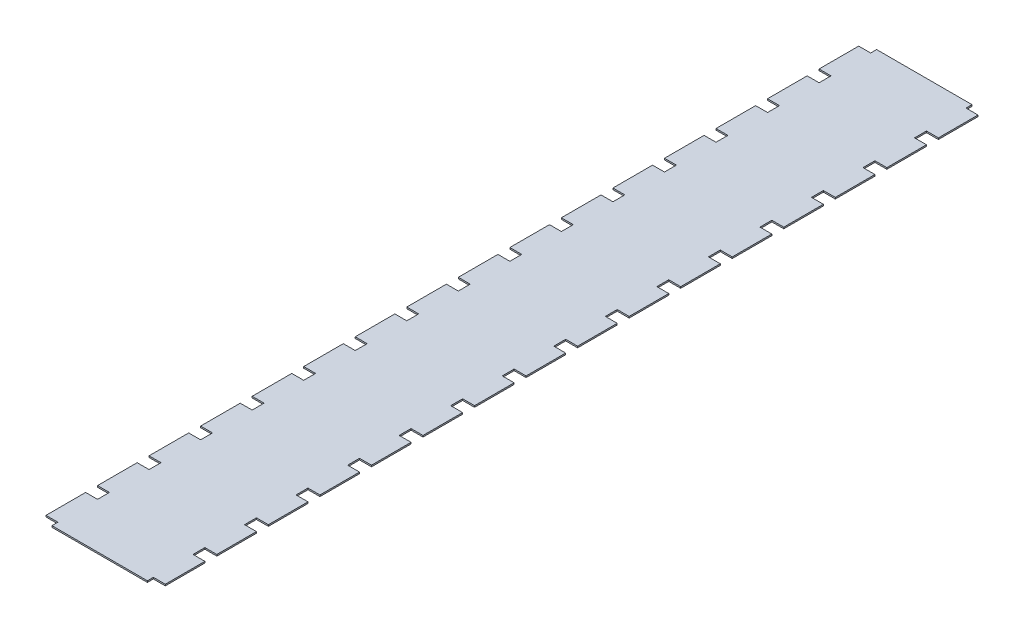
SolidWorks part; units mm, degrees
ref_plane "Front Plane" through (0, 0, 0) normal (0, 0, 1) x (1, 0, 0)
ref_plane "Top Plane" through (0, 0, 0) normal (0, 1, 0) x (1, 0, 0)
ref_plane "Right Plane" through (0, 0, 0) normal (1, 0, 0) x (0, 0, -1)
sketch "Sketch1" plane through (0, 0, 0) normal (0, 1, 0) x (1, 0, 0)
  line L0 (0, -150.6266) -> (0, 617.4694) construction
  line L1 (-63.5, 438.912) -> (63.5, 438.912)
  line L2 (-63.5, 438.912) -> (-63.5, -438.912)
  line L3 (-63.5, -438.912) -> (63.5, -438.912)
  line L4 (63.5, 438.912) -> (63.5, -438.912)
  line L5 (398.0134, 0) -> (-511.7315, 0) construction
  dimension "D1" = 877.824
  dimension "D2" = 127
extrude "Boss-Extrude1" add sketch "Sketch1" along normal blind 1.5875
sketch "Sketch2" plane through (0, 1.5875, 0) normal (0, 1, 0) x (1, 0, 0)
  line L1 (-63.5, 438.912) -> (-50.8, 438.912)
  line L2 (-63.5, 438.912) -> (-63.5, 432.562)
  line L3 (-63.5, 432.562) -> (-50.8, 432.562)
  line L4 (-50.8, 438.912) -> (-50.8, 432.562)
  line L5 (63.5, 438.912) -> (50.8, 438.912)
  line L6 (63.5, 438.912) -> (63.5, 432.562)
  line L7 (63.5, 432.562) -> (50.8, 432.562)
  line L8 (50.8, 438.912) -> (50.8, 432.562)
  dimension "D1" = 6.35
  dimension "D2" = 12.7
  dimension "D3" = 6.35
  dimension "D4" = 12.7
extrude "Cut-Extrude1" cut sketch "Sketch2" against normal through all
mirror "Mirror1" about plane through (0, 0, 0) normal (0, 0, 1) of "Cut-Extrude1"
sketch "Sketch3" plane through (0, 1.5875, 0) normal (0, 1, 0) x (1, 0, 0)
  line L0 (-63.5, 432.562) -> (-63.5, -432.562) construction
  line L1 (-63.5, 390.398) -> (-50.8, 390.398)
  line L2 (-63.5, 390.398) -> (-63.5, 377.698)
  line L3 (-63.5, 377.698) -> (-50.8, 377.698)
  line L4 (-50.8, 390.398) -> (-50.8, 377.698)
  line L5 (-63.5, 432.562) -> (-50.8, 432.562) construction
  dimension "D1" = 12.7
  dimension "D2" = 42.164
extrude "Cut-Extrude2" cut sketch "Sketch3" against normal through all
mirror "Mirror2" about plane through (0, 0, 0) normal (1, 0, 0) of "Cut-Extrude2"
pattern_linear "LPattern1" count 15 spacing 54.864 along (0, 0, 1) of "Mirror2", "Cut-Extrude2"
